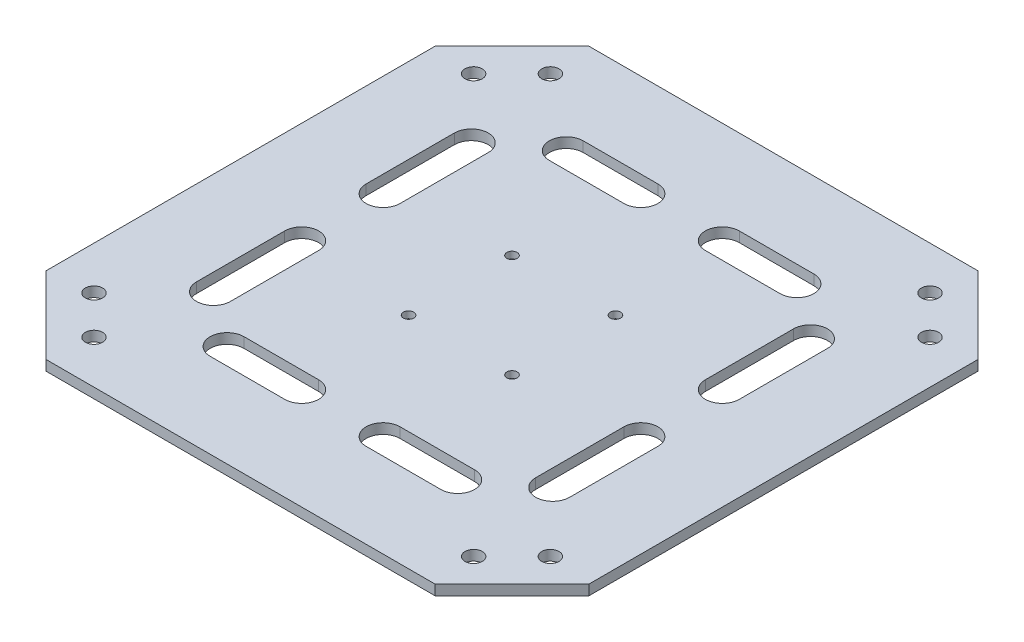
SolidWorks part; units mm, degrees
material "Custom Plastic"
ref_plane "Front Plane" through (0, 0, 0) normal (0, 0, 1) x (1, 0, 0)
ref_plane "Top Plane" through (0, 0, 0) normal (0, 1, 0) x (1, 0, 0)
ref_plane "Right Plane" through (0, 0, 0) normal (1, 0, 0) x (0, 0, -1)
sketch "Sketch1" plane through (0, 0, 0) normal (0, 1, 0) x (1, 0, 0)
  line L1 (80, 80) -> (-80, 80)
  line L2 (80, 80) -> (80, -80)
  line L3 (80, -80) -> (-80, -80)
  line L4 (-80, 80) -> (-80, -80)
  point P0 (0, 0)
  dimension "D1" = 160
  dimension "D2" = 80
  dimension "D3" = 80
extrude "Boss-Extrude1" add sketch "Sketch1" against normal blind 3
sketch "Sketch6" plane through (0, 0, 0) normal (0, 1, 0) x (1, 0, 0)
  line L0 (-80, -57.3726) -> (-57.3726, -80)
  line L1 (-80, 80) -> (-80, -80) construction
  line L2 (-80, -80) -> (80, -80) construction
  line L3 (-57.3726, -80) -> (-80, -80)
  line L4 (-80, -80) -> (-80, -57.3726)
  dimension "D1" = 45
  dimension "D2" = 32
extrude "Cut-Extrude2" cut sketch "Sketch6" against normal up to next
sketch "Sketch2" plane through (0, 0, 0) normal (0, 1, 0) x (1, 0, 0)
  line L0 (-67.2721, -55.9584) -> (-55.9584, -67.2721) construction
  line L1 (-68.6863, -68.6863) -> (-61.6152, -61.6152) construction
  line L5 (-57.3726, -80) -> (-80, -57.3726) construction
  circle A0 centre (-67.2721, -55.9584) radius 2.55
  circle A1 centre (-55.9584, -67.2721) radius 2.55
  dimension "D1" = 16
  dimension "D2" = 10
  dimension "D3" = 5.1
extrude "Cut-Extrude1" cut sketch "Sketch2" against normal up to next
mirror "Mirror2" about plane through (0, 0, 0) normal (1, 0, 0) of "Cut-Extrude2", "Cut-Extrude1" second plane through (0, 0, 0) second plane normal (0, 0, 1)
sketch "Sketch8" plane through (0, 0, 0) normal (0, 1, 0) x (1, 0, 0)
  line L1 (15.25, 15.25) -> (-15.25, 15.25) construction
  line L2 (15.25, 15.25) -> (15.25, -15.25) construction
  line L3 (15.25, -15.25) -> (-15.25, -15.25) construction
  line L4 (-15.25, 15.25) -> (-15.25, -15.25) construction
  line L5 (15.25, 15.25) -> (-15.25, -15.25) construction
  line L6 (15.25, -15.25) -> (-15.25, 15.25) construction
  circle A0 centre (-15.25, 15.25) radius 1.525
  circle A1 centre (-15.25, -15.25) radius 1.525
  circle A2 centre (15.25, -15.25) radius 1.525
  circle A3 centre (15.25, 15.25) radius 1.525
  point P0 (0, 0)
  dimension "D2" = 3.05
  dimension "D1" = 30.5
extrude "Cut-Extrude3" cut sketch "Sketch8" against normal up to next
sketch "Sketch9" plane through (0, 0, 0) normal (0, 1, 0) x (1, 0, 0)
  line L0 (-50, 38) -> (-50, 12) construction
  line L1 (-45, 38) -> (-45, 12)
  line L2 (-55, 38) -> (-55, 12)
  line L3 (-50, -12) -> (-50, -38) construction
  line L4 (-45, -12) -> (-45, -38)
  line L5 (-55, -12) -> (-55, -38)
  line L6 (-34, 50) -> (-12, 50) construction
  line L9 (-34, 55) -> (-12, 55)
  line L12 (-50, 12) -> (-50, -12) construction
  line L13 (-50, 0) -> (0, 0) construction
  line L14 (-34, 45) -> (-12, 45)
  line L15 (12, 50) -> (34, 50) construction
  line L16 (12, 55) -> (34, 55)
  line L17 (12, 45) -> (34, 45)
  line L18 (-12, 50) -> (12, 50) construction
  line L19 (0, 0) -> (0, 50) construction
  arc A0 (-45, 38) -> (-55, 38) centre (-50, 38) ccw
  arc A1 (-55, 12) -> (-45, 12) centre (-50, 12) ccw
  arc A2 (-45, -12) -> (-55, -12) centre (-50, -12) ccw
  arc A3 (-55, -38) -> (-45, -38) centre (-50, -38) ccw
  arc A8 (-34, 55) -> (-34, 45) centre (-34, 50) ccw
  arc A9 (-12, 45) -> (-12, 55) centre (-12, 50) ccw
  arc A10 (12, 55) -> (12, 45) centre (12, 50) ccw
  arc A11 (34, 45) -> (34, 55) centre (34, 50) ccw
  point P2 (-50, 25)
  point P7 (-50, -25)
  point P16 (-23, 50)
  point P21 (23, 50)
  dimension "D4" = 24
  dimension "D1" = 26
  dimension "D2" = 10
  dimension "D3" = 10
  dimension "D5" = 50
  dimension "D6" = 10
  dimension "D7" = 10
  dimension "D8" = 22
  dimension "D9" = 22
extrude "Cut-Extrude4" cut sketch "Sketch9" against normal up to next
mirror "Mirror3" about plane through (0, 0, 0) normal (0, 0, 1) of "Cut-Extrude4" second plane through (0, 0, 0) second plane normal (1, 0, 0)
sketch "Sketch10" plane through (0, -3, 0) normal (0, 1, 0) x (1, 0, 0)
  line L1 (15.25, 15.25) -> (-15.25, 15.25) construction
  line L2 (15.25, 15.25) -> (15.25, -15.25) construction
  line L3 (15.25, -15.25) -> (-15.25, -15.25) construction
  line L4 (-15.25, 15.25) -> (-15.25, -15.25) construction
  line L5 (15.25, 15.25) -> (-15.25, -15.25) construction
  line L6 (15.25, -15.25) -> (-15.25, 15.25) construction
  circle A0 centre (-15.25, 15.25) radius 2.85
  circle A1 centre (15.25, 15.25) radius 2.85
  circle A2 centre (15.25, -15.25) radius 2.85
  circle A3 centre (-15.25, -15.25) radius 2.85
  point P0 (0, 0)
  dimension "D1" = 5.7
extrude "Cut-Extrude6" cut sketch "Sketch10" along normal blind 1
equation "\"body_length\"= 160"
equation "\"D1@Sketch1\"=\"body_length\""
equation "\"D2@Sketch1\"=\"body_length\"/2"
equation "\"D3@Sketch1\"=\"body_length\"/2"
